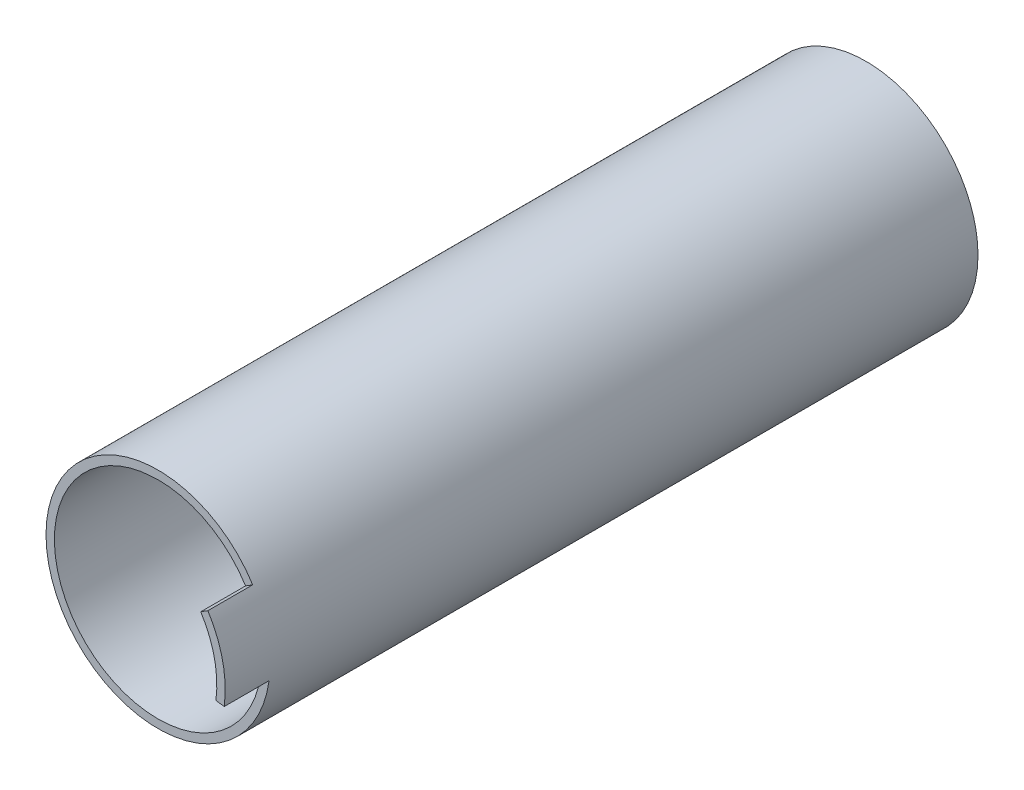
SolidWorks part; units mm, degrees
ref_plane "Спереди" through (0, 0, 0) normal (0, 0, 1) x (1, 0, 0)
ref_plane "Сверху" through (0, 0, 0) normal (0, 1, 0) x (1, 0, 0)
ref_plane "Справа" through (0, 0, 0) normal (1, 0, 0) x (0, 0, -1)
sketch "Эскиз2" plane through (0, 0, 0) normal (0, 0, 1) x (1, 0, 0)
  circle A0 centre (0, 0) radius 20
  circle A1 centre (0, 0) radius 18.5
  dimension "D1" = 40
  dimension "D2" = 37
extrude "Бобышка-Вытянуть1" add sketch "Эскиз2" along normal blind 126.4
sketch "Эскиз5" plane through (0, 0, 0) normal (0, 0, -1) x (-1, 0, 0)
  line L0 (0, 0) -> (0, 18.5) construction
  line L1 (0, 0) -> (2.9901, 18.2568) construction
  line L2 (0, 18.5) -> (0, 9.2195)
  line L3 (2.9901, 18.2568) -> (1.4901, 9.0983)
  circle A0 centre (0, 0) radius 18.5 construction
  arc A1 (0, 18.5) -> (2.9901, 18.2568) centre (0, 0) cw
  arc A2 (1.4901, 9.0983) -> (3.3687, 3.6948) centre (7.4112, 8.1286) ccw
  circle A3 centre (0, 0) radius 3
  arc A4 (-2.7273, 4.1907) -> (3.3687, 3.6948) centre (0, 0) ccw
  arc A5 (0, 9.2195) -> (-2.7273, 4.1907) centre (-6, 9.2195) cw
  point P16 (0, 5)
  dimension "D2" = 5
  dimension "D3" = 6
  dimension "D4" = 6
  dimension "D1" = 3
extrude "Бобышка-Вытянуть3" add sketch "Эскиз5" against normal through all
sketch "Sketch1" plane through (0, 0, 0) normal (0, 0, -1) x (-1, 0, 0)
  line L0 (0, 18.5) -> (2.9901, 18.2568)
  arc A2 (0, 18.5) -> (2.9901, 18.2568) centre (0, 0) ccw
  dimension "D1" = 18.5
extrude "Cut-Extrude1" cut sketch "Sketch1" against normal blind 59
sketch "Sketch2" plane through (0, 0, 126.4) normal (0, 0, 1) x (1, 0, 0)
  line L0 (0, 18.5) -> (-2.9901, 18.2568)
  arc A2 (0, 18.5) -> (-2.9901, 18.2568) centre (0, 0) cw
  dimension "D1" = 18.5
extrude "Cut-Extrude2" cut sketch "Sketch2" against normal blind 59
sketch "Sketch3" plane through (0, 0, 0) normal (0, 0, 1) x (1, 0, 0)
  line L0 (5, 0) -> (5, 16.7705)
  line L1 (-5, 0) -> (-5, 16.7705)
  circle A0 centre (0, 0) radius 5 construction
  circle A1 centre (0, 0) radius 3
  arc A2 (5, 0) -> (-5, 0) centre (0, 0) cw
  arc A3 (5, 16.7705) -> (-5, 16.7705) centre (0, 0) ccw
  arc A4 (-2.9901, 18.2568) -> (0, 18.5) centre (0, 0) ccw construction
  point P13 (0, 0)
  dimension "D1" = 10
  dimension "D2" = 6
  dimension "D3" = 1
sketch "Sketch6" plane through (0, 0, 126.4) normal (0, 0, 1) x (1, 0, 0)
  line L0 (20, 0) -> (0, 0) construction
  line L2 (0, 0) -> (19.8206, -2.6728) construction
  line L3 (0, 0) -> (16.9015, 10.6929) construction
  line L4 (16.9015, 10.6929) -> (15.6339, 9.891)
  line L5 (19.8206, -2.6728) -> (18.3341, -2.4723)
  circle A1 centre (0, 0) radius 20 construction
  arc A3 (16.9015, 10.6929) -> (19.8206, -2.6728) centre (0, 0) cw
  arc A5 (15.6339, 9.891) -> (18.3341, -2.4723) centre (0, 0) cw
  arc A6 (-2.9901, 18.2568) -> (0, 18.5) centre (0, 0) ccw construction
  dimension "D1" = 40
  dimension "D2" = 7.68
extrude "Boss-Extrude4" add sketch "Sketch6" along normal blind 8
extrude "Boss-Extrude6" add sketch "Sketch3" along normal offset from surface (58.6 mm away) 0.4 separate body up to face at (-0.7247, 8.9083, 59)
